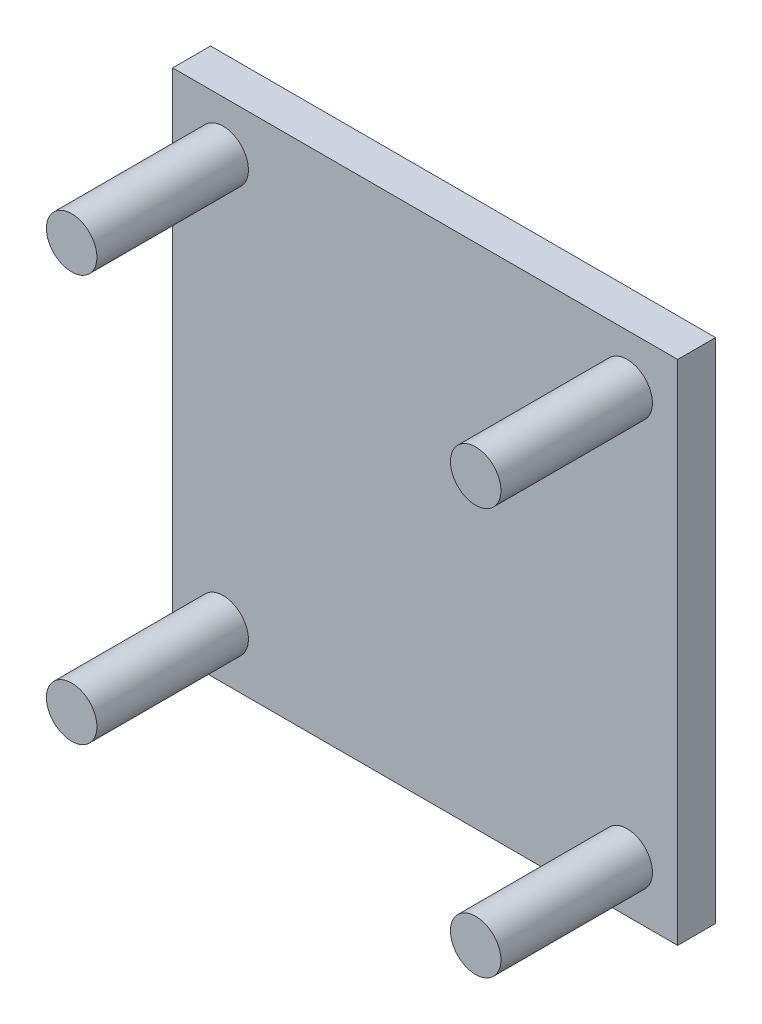
SolidWorks part; units mm, degrees
ref_plane "Спереди" through (0, 0, 0) normal (0, 0, 1) x (1, 0, 0)
ref_plane "Сверху" through (0, 0, 0) normal (0, 1, 0) x (1, 0, 0)
ref_plane "Справа" through (0, 0, 0) normal (1, 0, 0) x (0, 0, -1)
sketch "Эскиз1" plane through (0, 0, 0) normal (0, 0, 1) x (1, 0, 0)
  line L0 (-20, -20.0967) -> (20, -20.0967)
  line L1 (20, -20.0967) -> (20, 20.0967)
  line L2 (20, 20.0967) -> (-20, 20.0967)
  line L3 (-20, 20.0967) -> (-20, -20.0967)
extrude "Former_base" add sketch "Эскиз1" along normal blind 3
sketch "Эскиз2" plane through (0, 0, 0) normal (0, 0, 1) x (1, 0, 0)
  circle A0 centre (-16, -16.0967) radius 2
  circle A1 centre (-16, 16.0967) radius 2
  circle A2 centre (16, -16.0967) radius 2
  circle A3 centre (16, 16.0967) radius 2
extrude "Former_posts" add sketch "Эскиз2" along normal blind 12 from offset 3
